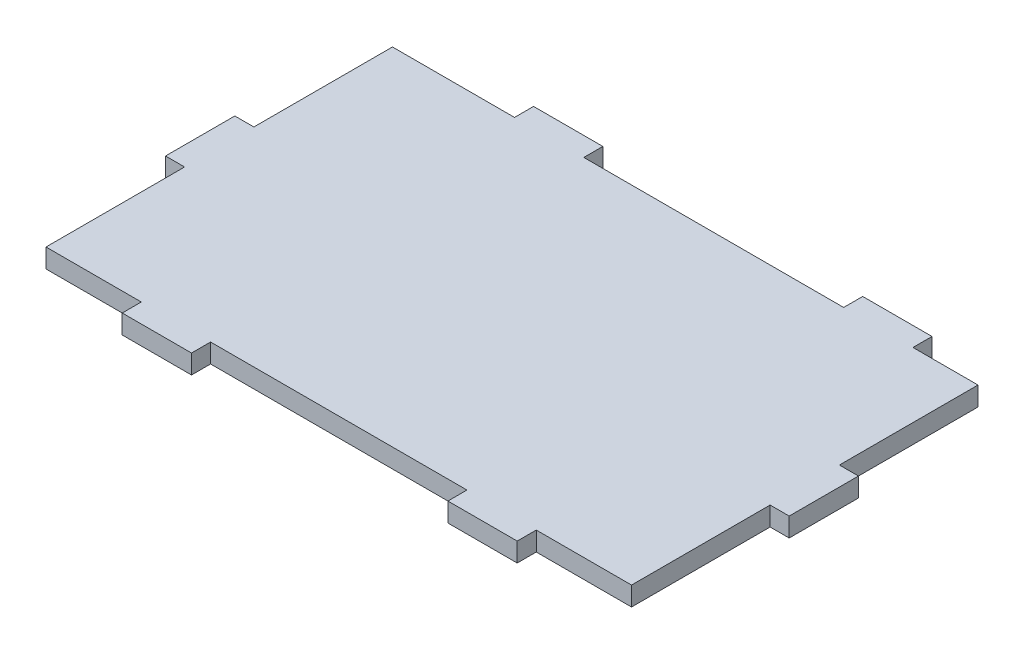
SolidWorks part; units mm, degrees
ref_plane "Front Plane" through (0, 0, 0) normal (0, 0, 1) x (1, 0, 0)
ref_plane "Top Plane" through (0, 0, 0) normal (0, 1, 0) x (1, 0, 0)
ref_plane "Right Plane" through (0, 0, 0) normal (1, 0, 0) x (0, 0, -1)
sketch "Sketch1" plane through (0, 0, 0) normal (0, 1, 0) x (1, 0, 0)
  line L0 (5.5, 104.5) -> (40.7245, 104.5)
  line L1 (33, -1) -> (53, -1)
  line L5 (174.5, 4.5) -> (174.5, 44.5)
  line L6 (5.5, 4.5) -> (33, 4.5)
  line L7 (5.5, 4.5) -> (5.5, 44.5)
  line L8 (40.7245, 110) -> (40.7245, 104.5)
  line L9 (95, 54.5) -> (180, 54.5) construction
  line L10 (60.7245, 110) -> (60.7245, 104.5)
  line L11 (53, -1) -> (53, 4.5)
  line L12 (174.5, 64.5) -> (180, 64.5)
  line L13 (135.7245, 110) -> (155.7245, 110)
  line L14 (174.5, 44.5) -> (180, 44.5)
  line L15 (33, -1) -> (33, 4.5)
  line L16 (5.5, 44.5) -> (0, 44.5)
  line L17 (5.5, 64.5) -> (0, 64.5)
  line L18 (60.7245, 104.5) -> (135.7245, 104.5)
  line L19 (60.7245, 110) -> (60.7245, 104.5) construction
  line L20 (53, 4.5) -> (127, 4.5)
  line L22 (174.5, 64.5) -> (174.5, 104.5)
  line L24 (5.5, 64.5) -> (5.5, 104.5)
  line L27 (0, 64.5) -> (0, 44.5)
  line L29 (0, 64.5) -> (5.5, 64.5) construction
  line L30 (0, 44.5) -> (5.5, 44.5) construction
  line L31 (40.7245, 110) -> (60.7245, 110)
  line L32 (180, 64.5) -> (180, 44.5)
  line L33 (155.7245, 110) -> (155.7245, 104.5)
  line L34 (135.7245, 110) -> (135.7245, 104.5)
  line L35 (127, -1) -> (127, 4.5)
  line L36 (147, -1) -> (147, 4.5)
  line L37 (127, -1) -> (147, -1)
  line L38 (155.7245, 104.5) -> (174.5, 104.5)
  line L39 (147, 4.5) -> (174.5, 4.5)
  line L40 (0, 4.5) -> (180, 4.5) construction
  line L41 (53, 4.5) -> (53, -1) construction
  line L42 (33, 4.5) -> (33, -1) construction
  line L43 (127, 4.5) -> (127, -1) construction
  line L44 (147, 4.5) -> (147, -1) construction
  line L45 (174.5, 64.5) -> (180, 64.5) construction
  line L47 (155.7245, 110) -> (155.7245, 104.5) construction
  line L48 (135.7245, 110) -> (135.7245, 104.5) construction
  line L51 (0, 104.5) -> (180, 104.5) construction
  line L52 (-3.5, -1) -> (183.5, -1) construction
  line L53 (0, 110) -> (180, 110) construction
  dimension "D4" = 20
  dimension "D6" = 20
  dimension "D7" = 10
  dimension "D9" = 5.5
  dimension "D10" = 5.5
  dimension "D11" = 5.5
extrude "Boss-Extrude1" add sketch "Sketch1" along normal blind 5.5 contours L32 L12 L22 L18 L10 L31 L8 L0 L24 L17 L27 L16 L7 L6 L15 L1 L11 L20 L5 L14
